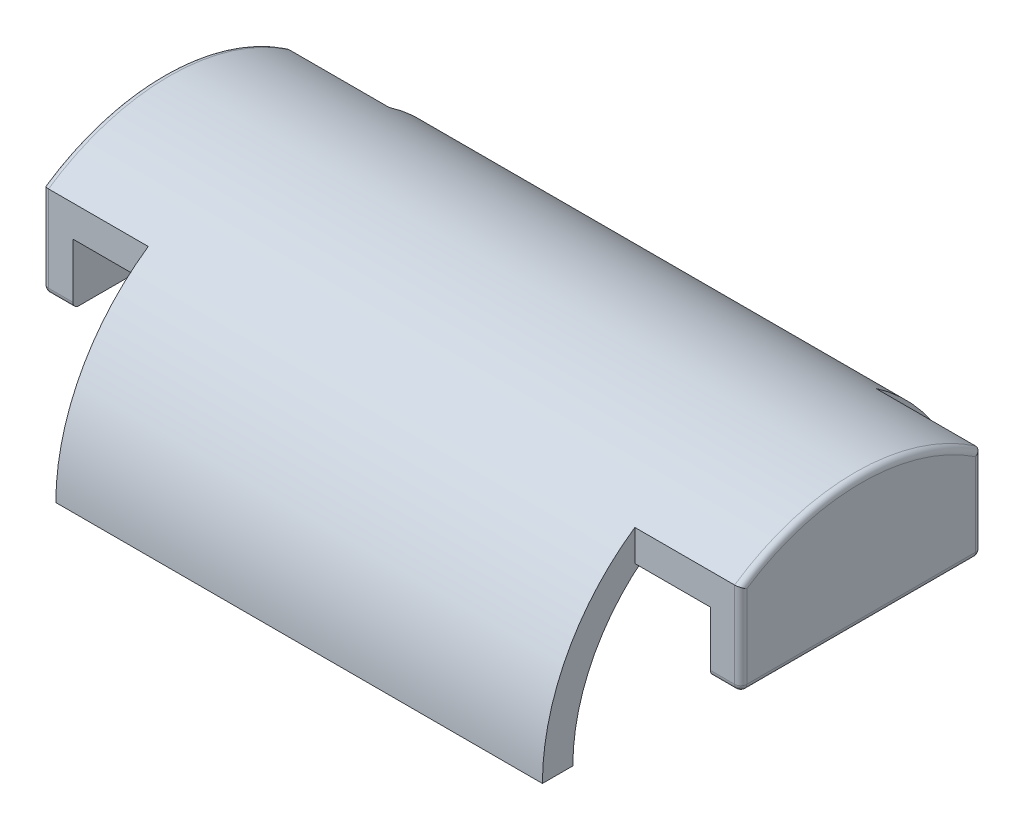
SolidWorks part; units mm, degrees
ref_plane "Front Plane" through (0, 0, 0) normal (0, 0, 1) x (1, 0, 0)
ref_plane "Top Plane" through (0, 0, 0) normal (0, 1, 0) x (1, 0, 0)
ref_plane "Right Plane" through (0, 0, 0) normal (1, 0, 0) x (0, 0, -1)
sketch "Sketch1" plane through (0, 0, 0) normal (0, 0, 1) x (1, 0, 0)
  line L0 (20.2, 0) -> (26.2, 0)
  line L1 (-20.2, 15) -> (20.2, 15)
  line L2 (-20.2, 15) -> (-20.2, 0)
  line L4 (20.2, 15) -> (20.2, 0)
  line L5 (-26.2, 17.5) -> (26.2, 17.5)
  line L6 (-26.2, 17.5) -> (-26.2, 0)
  line L7 (-26.2, 0) -> (-20.2, 0)
  line L8 (26.2, 17.5) -> (26.2, 0)
  line L9 (0, 0) -> (-43.9835, 0) construction
  dimension "D1" = 15
  dimension "D2" = 40.4
  dimension "D3" = 20.2
  dimension "D4" = 2.5
  dimension "D5" = 6
  dimension "D6" = 6
revolve "Revolve1" add sketch "Sketch1" angle 360 about L9
sketch "Sketch2" plane through (-26.2, 0, 0) normal (-1, 0, 0) x (0, 0, 1)
  line L0 (-17.5, 0) -> (17.5, 0)
  circle A1 centre (0, 0) radius 17.5
  arc A2 (-17.5, 0) -> (17.5, 0) centre (0, 0) ccw
  dimension "D1" = 0
extrude "lower half cut" cut sketch "Sketch2" against normal through all
sketch "Sketch3" plane through (-26.2, 0, 0) normal (-1, 0, 0) x (0, 0, 1)
  line L1 (-17.5, 0) -> (17.5, 0)
  line L2 (-17.5, 0) -> (17.5, 0)
  line L5 (0, -1000) -> (0, 49000) construction
  line L6 (-9.9, 11.8614) -> (9.9, 11.8614)
  line L7 (9.9, 14.4305) -> (9.9, 11.8614)
  line L8 (-9.9, 14.4305) -> (-9.9, 11.8614)
  arc A1 (17.5, 0) -> (-17.5, 0) centre (0, 0) ccw
  arc A3 (17.5, 0) -> (-17.5, 0) centre (0, 0) ccw construction
  arc A4 (17.5, 0) -> (9.9, 14.4305) centre (0, 0) ccw
  arc A5 (-9.9, 14.4305) -> (-17.5, 0) centre (0, 0) ccw
  dimension "D2" = 19.8
  dimension "D3" = 11.8614
  dimension "D1" = 0
extrude "side shell cut 1" cut sketch "Sketch3" against normal blind 6.2
sketch "Sketch4" plane through (26.2, 0, 0) normal (1, 0, 0) x (0, 0, -1)
  line L18 (-17.5, 0) -> (17.5, 0) construction
  line L19 (9.9, 14.4305) -> (9.9, 11.8614) construction
  line L20 (9.9, 11.8614) -> (-9.9, 11.8614) construction
  line L21 (-9.9, 11.8614) -> (-9.9, 14.4305) construction
  line L22 (-17.5, 0) -> (17.5, 0)
  line L23 (9.9, 14.4305) -> (9.9, 11.8614)
  line L24 (9.9, 11.8614) -> (-9.9, 11.8614)
  line L25 (-9.9, 11.8614) -> (-9.9, 14.4305)
  arc A3 (17.5, 0) -> (-17.5, 0) centre (0, 0) ccw construction
  arc A8 (17.5, 0) -> (9.9, 14.4305) centre (0, 0) ccw
  arc A10 (-9.9, 14.4305) -> (-17.5, 0) centre (0, 0) ccw
extrude "side shell cut 2" cut sketch "Sketch4" against normal blind 6.2
sketch "Sketch5" plane through (-26.2, 0, 0) normal (-1, 0, 0) x (0, 0, 1)
  line L3 (-9.9, 14.4305) -> (-9.9, 11.8614)
  line L4 (-9.9, 14.4305) -> (-9.9, 11.8614)
  line L5 (-9.9, 11.8614) -> (9.9, 11.8614)
  line L9 (-9.9, 11.8614) -> (-9.9, 6.8614)
  line L10 (9.9, 11.8614) -> (9.9, 6.8614)
  line L11 (-9.9, 6.8614) -> (9.9, 6.8614)
  line L13 (9.9, 11.8614) -> (9.9, 14.4305)
  line L14 (9.9, 11.8614) -> (9.9, 14.4305)
  arc A1 (9.9, 14.4305) -> (-9.9, 14.4305) centre (0, 0) ccw
  arc A2 (9.9, 14.4305) -> (-9.9, 14.4305) centre (0, 0) ccw
  dimension "D2" = 5
  dimension "D3" = 5
  dimension "D1" = 0
extrude "Boss-Extrude3" add sketch "Sketch5" along normal blind 2.5
sketch "Sketch7" plane through (26.2, 0, 0) normal (1, 0, 0) x (0, 0, -1)
  line L9 (-9.9, 6.8614) -> (9.9, 6.8614)
  line L10 (-9.9, 14.4305) -> (-9.9, 6.8614)
  line L11 (9.9, 6.8614) -> (9.9, 14.4305)
  line L12 (-9.9, 6.8614) -> (9.9, 6.8614)
  line L13 (-9.9, 14.4305) -> (-9.9, 6.8614)
  line L14 (9.9, 6.8614) -> (9.9, 14.4305)
  arc A3 (9.9, 14.4305) -> (-9.9, 14.4305) centre (0, 0) ccw
  arc A4 (9.9, 14.4305) -> (-9.9, 14.4305) centre (0, 0) ccw
  dimension "D1" = 0
extrude "Boss-Extrude4" add sketch "Sketch7" along normal blind 2.5
fillet "Fillet2" radius 0.5 12 edges at (-28.7, 10.646, -9.9) (-28.7, 17.5, 0) (-28.7, 10.646, 9.9) (-28.7, 6.8614, 0) (28.7, 6.8614, 0) (28.7, 10.646, 9.9) (28.7, 17.5, 0) (28.7, 10.646, -9.9) (-27.45, 6.8614, 9.9) (-27.45, 6.8614, -9.9) (27.45, 6.8614, 9.9) (27.45, 6.8614, -9.9)
